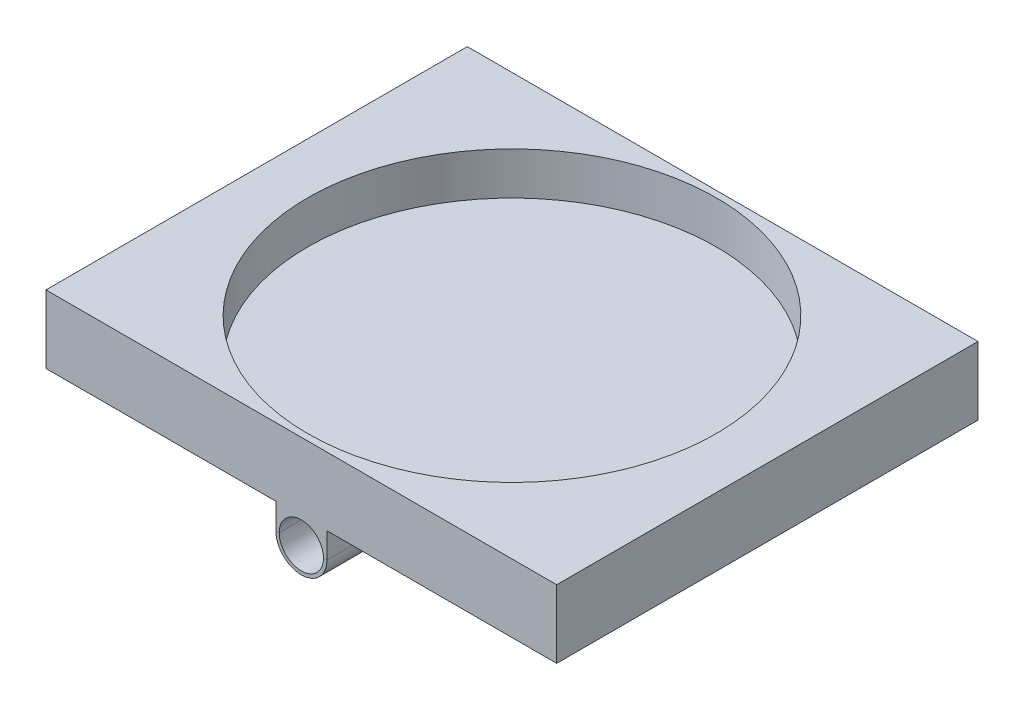
SolidWorks part; units mm, degrees
ref_plane "Front Plane" through (0, 0, 0) normal (0, 0, 1) x (1, 0, 0)
ref_plane "Top Plane" through (0, 0, 0) normal (0, 1, 0) x (1, 0, 0)
ref_plane "Right Plane" through (0, 0, 0) normal (1, 0, 0) x (0, 0, -1)
sketch "Sketch2" plane through (0, 0, 0) normal (0, 0, 1) x (1, 0, 0)
  line L0 (0, 0) -> (-3, 0) construction
  circle A0 centre (0, 0) radius 3
  dimension "D1" = 6
extrude "Boss-Extrude1" add sketch "Sketch2" along normal blind 49.5
sketch "Sketch3" plane through (0, 0, 49.5) normal (0, 0, 1) x (1, 0, 0)
  line L0 (3, 0) -> (3, 3)
  line L1 (-3, 0) -> (-3, 3)
  line L2 (-3, 3) -> (-30, 3)
  line L3 (-30, 3) -> (-30, 11)
  line L4 (-30, 11) -> (30, 11)
  line L5 (30, 11) -> (30, 3)
  line L6 (30, 3) -> (3, 3)
  line L7 (-3, 0) -> (0, 0) construction
  line L8 (0, 0) -> (3, 0) construction
  line L10 (-3, 0) -> (-2.6, 0)
  line L11 (2.6, 0) -> (3, 0)
  circle A0 centre (0, 0) radius 3 construction
  arc A2 (2.6, 0) -> (-2.6, 0) centre (0, 0) ccw
  dimension "D3" = 5.2
  dimension "D1" = 60
  dimension "D2" = 11
sketch "Sketch4" plane through (0, 0, 49.5) normal (0, 0, 1) x (1, 0, 0)
  circle A0 centre (0, 0) radius 2.6
  dimension "D1" = 5.2
extrude "Cut-Extrude1" cut sketch "Sketch4" against normal blind 49.5
sketch "Sketch5" plane through (0, 0, 49.5) normal (0, 0, 1) x (1, 0, 0)
  line L0 (0, 0) -> (-5.4454, 0) construction
  line L1 (-5.4454, 0) -> (13.1341, 0)
  line L2 (-5.4454, 0) -> (-5.4454, 4.3421)
  line L3 (-5.4454, 4.3421) -> (13.1341, 4.3421)
  line L4 (13.1341, 0) -> (13.1341, 4.3421)
  line L5 (0, 0) -> (0, 4.3421) construction
  dimension "D1" = 18.5795
  dimension "D2" = 4.3421
  dimension "D3" = 6.9646
extrude "Cut-Extrude2" cut sketch "Sketch5" against normal blind 49.5
extrude "Boss-Extrude2" add sketch "Sketch3" against normal blind 49.5 separate body
sketch "Sketch6" plane through (0, 11, 0) normal (0, 1, 0) x (1, 0, 0)
  line L0 (-30, -49.5) -> (-30, -24.75) construction
  line L1 (-30, 0) -> (-30, -49.5) construction
  line L2 (-30, -24.75) -> (30, -24.75) construction
  line L4 (30, 0) -> (30, -49.5) construction
  circle A1 centre (0, -24.75) radius 24
  dimension "D1" = 48
extrude "Cut-Extrude3" cut sketch "Sketch6" against normal blind 5
sketch "Sketch9" plane through (3, 0, 0) normal (1, 0, 0) x (0, 0, -1)
  line L0 (-49.5, -3) -> (0, -3) construction
  line L1 (-24.75, -3) -> (-24.75, 0) construction
  line L2 (0, 0) -> (-49.5, 0) construction
  circle A0 centre (-24.75, 0) radius 1
  dimension "D1" = 2
extrude "Cut-Extrude5" cut sketch "Sketch9" against normal blind 10
